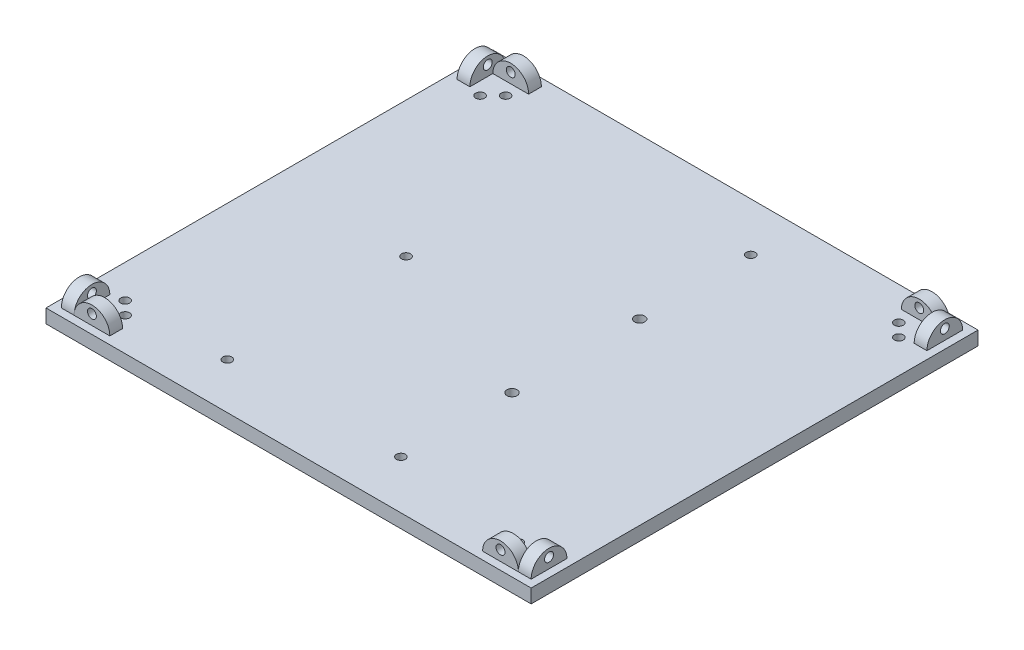
SolidWorks part; units mm, degrees
ref_plane "Front Plane" through (0, 0, 0) normal (0, 0, 1) x (1, 0, 0)
ref_plane "Top Plane" through (0, 0, 0) normal (0, 1, 0) x (1, 0, 0)
ref_plane "Right Plane" through (0, 0, 0) normal (1, 0, 0) x (0, 0, -1)
sketch "Sketch1" plane through (0, 0, 0) normal (0, 1, 0) x (1, 0, 0)
  line L1 (-26.0644, -19.3857) -> (126.4356, -19.3857) construction
  line L2 (-26.0644, -19.3857) -> (-26.0644, 30.6143) construction
  line L3 (-26.0644, 30.6143) -> (126.4356, 30.6143) construction
  line L4 (126.4356, -19.3857) -> (126.4356, 30.6143) construction
  line L5 (-143.0644, 90.1143) -> (40.9356, 90.1143) construction
  line L6 (40.9356, -78.8857) -> (40.9356, 90.1143) construction
  line L10 (-146.0644, 93.1143) -> (43.9356, 93.1143)
  line L11 (43.9356, -81.8857) -> (43.9356, 93.1143)
  line L12 (-146.0644, -81.8857) -> (43.9356, -81.8857)
  line L13 (-146.0644, -81.8857) -> (-146.0644, 93.1143)
  line L14 (-143.0644, -78.8857) -> (40.9356, -78.8857) construction
  line L15 (-143.0644, -78.8857) -> (-143.0644, 90.1143) construction
  line L17 (113.9356, 62.2405) -> (53.9356, 62.2405) construction
  line L18 (113.9356, 62.2405) -> (113.9356, 2.2405) construction
  line L19 (113.9356, 2.2405) -> (53.9356, 2.2405) construction
  line L20 (53.9356, 62.2405) -> (53.9356, 2.2405) construction
  line L21 (-51.0644, 90.1143) -> (-51.0644, -78.8857) construction
  line L22 (-143.0644, 5.6143) -> (40.9356, 5.6143) construction
  line L23 (-26.0644, -19.3857) -> (-26.0644, -67.8857) construction
  line L24 (-26.0644, -67.8857) -> (-26.0644, -62.8857) construction
  line L25 (-26.0644, 30.6143) -> (-26.0644, 79.1143) construction
  line L26 (-26.0644, 79.1143) -> (-26.0644, 74.1143) construction
  line L27 (-93.0644, 11.1143) -> (-93.0644, -68.8857) construction
  line L28 (-118.0644, 11.1143) -> (-68.0644, 11.1143) construction
  line L29 (-118.0644, 11.1143) -> (-118.0644, -68.8857) construction
  line L30 (-118.0644, -68.8857) -> (-68.0644, -68.8857) construction
  line L31 (-68.0644, 11.1143) -> (-68.0644, -68.8857) construction
  line L32 (-118.0644, 11.1143) -> (-68.0644, -68.8857) construction
  line L33 (-118.0644, -68.8857) -> (-68.0644, 11.1143) construction
  line L34 (-93.0644, 11.1143) -> (-93.0644, 6.1143) construction
  line L35 (-93.0644, -68.8857) -> (-93.0644, -63.8857) construction
  circle A0 centre (-26.0644, 30.6143) radius 2
  circle A1 centre (-26.0644, -19.3857) radius 2
  circle A2 centre (-26.0644, -62.8857) radius 1.75
  circle A3 centre (-26.0644, 74.1143) radius 1.75
  circle A4 centre (-93.0644, 6.1143) radius 1.75
  circle A5 centre (-93.0644, -63.8857) radius 1.75
  point P29 (-93.0644, -28.8857)
  dimension "D6" = 4
  dimension "D14" = 3.5
  dimension "D15" = 5
  dimension "D17" = 3.5
  dimension "D22" = 3.5
  dimension "D23" = 3.5
  dimension "D1" = 50
  dimension "D2" = 80
  dimension "D4" = 200
  dimension "D5" = 59.5
  dimension "D9" = 175
  dimension "D10" = 190
  dimension "D11" = 60
  dimension "D12" = 70
  dimension "D13" = 48.5
  dimension "D3" = 3
  dimension "D8" = 5
  dimension "D16" = 48.5
  dimension "D18" = 50
  dimension "D19" = 25
  dimension "D20" = 10
  dimension "D21" = 5
  dimension "D7" = 2
extrude "Base" add sketch "Sketch1" against normal blind 5.4
ref_plane "Plane1" through (-143.0644, 0, 0) normal (1, 0, 0) x (0, 0, -1)
sketch "Sketch3" plane through (-143.0644, 0, 0) normal (1, 0, 0) x (0, 0, -1)
  line L1 (-78.8857, 0) -> (90.1143, 0) construction
  line L2 (90.1143, 0) -> (83.1143, 0) construction
  line L3 (76.1143, 0) -> (90.1143, 0)
  line L4 (-78.8857, 0) -> (-64.8857, 0)
  line L5 (-71.8857, 7) -> (-71.8857, 0) construction
  line L6 (83.1143, 7) -> (83.1143, 0) construction
  line L7 (-78.8857, 0) -> (90.1143, 0) construction
  arc A0 (90.1143, 0) -> (76.1143, 0) centre (83.1143, 0) ccw
  arc A1 (-64.8857, 0) -> (-78.8857, 0) centre (-71.8857, 0) ccw
  circle A2 centre (-71.8857, 4) radius 1.75
  circle A3 centre (83.1143, 4) radius 1.75
  point P18 (93.1143, 0)
  dimension "D1" = 14
  dimension "D2" = 3.5
  dimension "D4" = 3.5
  dimension "D3" = 3
  dimension "D5" = 4
  dimension "D6" = 14
extrude "Long_Side_connectors" add sketch "Sketch3" along normal blind 5
ref_plane "Plane2" through (0, 0, 78.8857) normal (0, 0, 1) x (1, 0, 0)
sketch "Sketch4" plane through (0, 0, 78.8857) normal (0, 0, 1) x (1, 0, 0)
  line L1 (-138.0644, 0) -> (-124.0644, 0)
  line L2 (-138.0644, 0) -> (-124.0644, 0)
  line L3 (-131.0644, 7) -> (-131.0644, 0) construction
  arc A0 (-124.0644, 0) -> (-138.0644, 0) centre (-131.0644, 0) ccw
  circle A1 centre (-131.0644, 4) radius 1.75
  dimension "D1" = 14
  dimension "D2" = 4
extrude "Short_side_connectors" add sketch "Sketch4" against normal blind 5 contours A0 L3 A1 L2 | L3 A0 L1 A1
ref_plane "Plane6" through (0, 0, -5.6143) normal (0, 0, 1) x (1, 0, 0)
mirror "Mirror1" about plane through (0, 0, -5.6143) normal (0, 0, 1) of "Short_side_connectors"
ref_plane "Plane5" through (-51.0644, 0, 0) normal (1, 0, 0) x (0, 0, -1)
mirror "Mirror3" about plane through (-51.0644, 0, 0) normal (1, 0, 0) of "Long_Side_connectors", "Mirror1", "Short_side_connectors"
sketch "Sketch6" plane through (0, 0, 0) normal (0, 1, 0) x (1, 0, 0)
  line L0 (126.4356, -19.3857) -> (126.4356, 30.6143) construction
  line L1 (136.4356, -62.7595) -> (216.4356, -62.7595)
  line L2 (136.4356, -62.7595) -> (136.4356, -12.7595)
  line L3 (136.4356, -12.7595) -> (216.4356, -12.7595)
  line L4 (216.4356, -62.7595) -> (216.4356, -12.7595)
  line L5 (136.4356, -62.7595) -> (216.4356, -12.7595) construction
  line L6 (136.4356, -12.7595) -> (216.4356, -62.7595) construction
  line L7 (113.9356, 2.2405) -> (53.9356, 2.2405) construction
  point P0 (176.4356, -37.7595)
  point P9 (83.9356, 2.2405)
  dimension "D1" = 50
  dimension "D2" = 80
  dimension "D3" = 10
  dimension "D4" = 15
extrude "Estop_relay" [suppressed] add sketch "Sketch6" along normal blind 2 contours L3 L4 L1 L2
sketch "Sketch8" [suppressed] plane through (0, 2, 0) normal (0, 1, 0) x (1, 0, 0)
  line L0 (38.9356, -37.7595) -> (118.9356, -37.7595) construction
  line L1 (38.9356, -62.7595) -> (38.9356, -12.7595) construction
  line L2 (118.9356, -62.7595) -> (118.9356, -12.7595) construction
  line L3 (38.9356, -37.7595) -> (43.9356, -37.7595) construction
  line L4 (78.9356, -12.7595) -> (78.9356, -62.7595) construction
  line L5 (38.9356, -12.7595) -> (118.9356, -12.7595) construction
  line L6 (38.9356, -62.7595) -> (118.9356, -62.7595) construction
  circle A0 centre (43.9356, -37.7595) radius 1.77
  circle A1 centre (113.9356, -37.7595) radius 1.77
  dimension "D2" = 3.54
  dimension "D1" = 5
extrude "Estop_bolts" [suppressed] cut sketch "Sketch8" against normal blind 5.3
sketch "Sketch9" plane through (0, 0, 0) normal (0, 1, 0) x (1, 0, 0)
  line L0 (-128.0644, 30.1143) -> (-128.0644, 5.1143) construction
  line L1 (-120.5644, 30.1143) -> (-120.5644, 5.1143)
  line L2 (-135.5644, 30.1143) -> (-135.5644, 5.1143)
  line L3 (-143.0644, 90.1143) -> (40.9356, 90.1143) construction
  line L4 (-143.0644, -78.8857) -> (-143.0644, 90.1143) construction
  arc A0 (-120.5644, 30.1143) -> (-135.5644, 30.1143) centre (-128.0644, 30.1143) ccw
  arc A1 (-135.5644, 5.1143) -> (-120.5644, 5.1143) centre (-128.0644, 5.1143) ccw
  point P2 (-128.0644, 17.6143)
  dimension "D1" = 25
  dimension "D2" = 15
  dimension "D3" = 60
  dimension "D4" = 15
extrude "Cut-Extrude4" [suppressed] cut sketch "Sketch9" against normal up to next contours A0 L2 A1 L1
sketch "Sketch10" [suppressed] plane through (0, 0, 0) normal (0, 1, 0) x (1, 0, 0)
  line L0 (-126.8751, 25.1928) -> (-127.2079, -70.1564) construction
  line L1 (-120.5644, 30.1143) -> (-120.5644, 5.1143) construction
  text T0 "Power"
  text T1 "  M-     M+    B-    B+    Bd   - Bd+  Bed_out+   -\r\n"
  dimension "D1" = 0.2
extrude "Text" [suppressed] cut sketch "Sketch10" against normal blind 1 and the other way through all
sketch "Sketch11" plane through (0, 0, 0) normal (0, 1, 0) x (1, 0, 0)
  line L0 (-138.0644, -73.8857) -> (-124.0644, -73.8857) construction
  line L1 (-133.0644, -68.8857) -> (-128.0644, -68.8857) construction
  line L2 (-133.0644, -68.8857) -> (-133.0644, -63.8857) construction
  line L3 (-133.0644, -63.8857) -> (-128.0644, -63.8857) construction
  line L4 (-128.0644, -68.8857) -> (-128.0644, -63.8857) construction
  line L5 (-138.0644, -73.8857) -> (-138.0644, -64.8857) construction
  line L6 (-138.0644, 85.1143) -> (-124.0644, 85.1143) construction
  line L7 (-133.0644, 80.1143) -> (-128.0644, 80.1143) construction
  line L8 (-133.0644, 80.1143) -> (-133.0644, 75.1143) construction
  line L9 (-133.0644, 75.1143) -> (-128.0644, 75.1143) construction
  line L10 (-128.0644, 80.1143) -> (-128.0644, 75.1143) construction
  line L11 (-138.0644, 76.1143) -> (-138.0644, 85.1143) construction
  line L12 (-51.0644, -85.25) -> (-51.0644, 85.25) construction
  circle A0 centre (-133.0644, -63.8857) radius 1.75
  circle A1 centre (-128.0644, -68.8857) radius 1.75
  circle A2 centre (-133.0644, 75.1143) radius 1.75
  circle A3 centre (-128.0644, 80.1143) radius 1.75
  circle A4 centre (30.9356, -63.8857) radius 1.75
  circle A5 centre (25.9356, -68.8857) radius 1.75
  circle A6 centre (30.9356, 75.1143) radius 1.75
  circle A7 centre (25.9356, 80.1143) radius 1.75
  dimension "D3" = 3.5
  dimension "D4" = 3.5
  dimension "D8" = 5
  dimension "D1" = 5
  dimension "D2" = 5
  dimension "D5" = 5
  dimension "D6" = 5
  dimension "4" = 5
  dimension "D7" = 5
  dimension "D9" = 5
extrude "Cut-Extrude6" cut sketch "Sketch11" along normal through all from surface at -5.4 starting at face at (-93.0644, -5.4, 65.6357)
